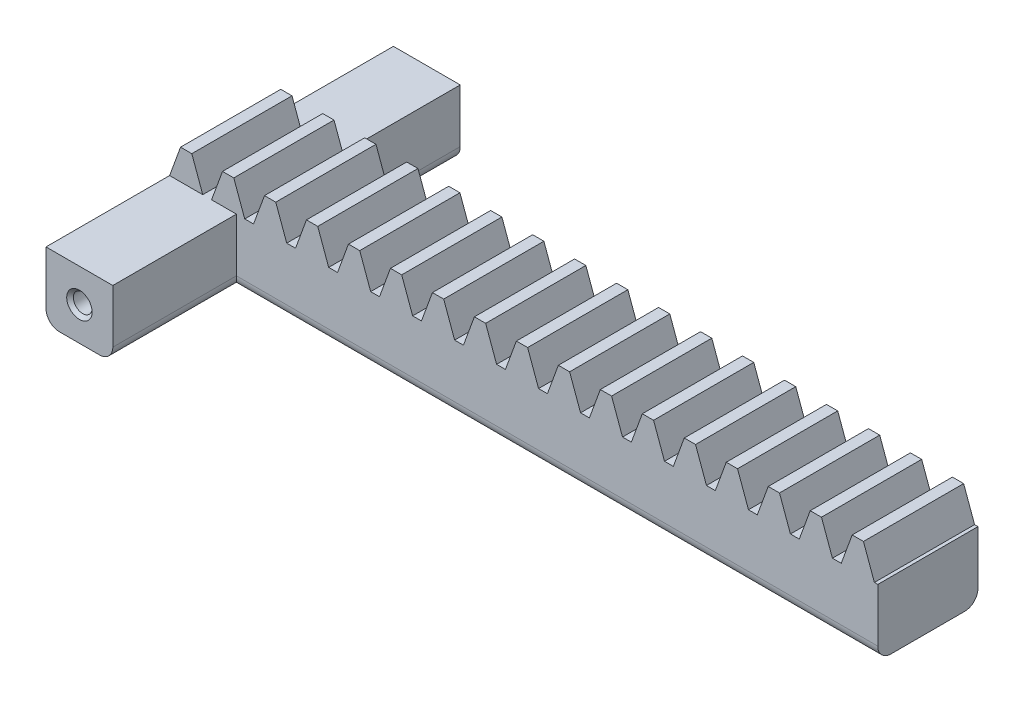
SolidWorks part; units mm, degrees
ref_plane "前视基准面" through (0, 0, 0) normal (0, 0, 1) x (1, 0, 0)
ref_plane "上视基准面" through (0, 0, 0) normal (0, 1, 0) x (1, 0, 0)
ref_plane "右视基准面" through (0, 0, 0) normal (1, 0, 0) x (0, 0, -1)
sketch "草图1" plane through (0, 0, 0) normal (0, 0, 1) x (1, 0, 0)
  line L1 (0, 0) -> (106, 0)
  line L2 (0, 0) -> (0, -10)
  line L3 (0, -10) -> (106, -10)
  line L4 (106, 0) -> (106, -10)
  dimension "D1" = 10
  dimension "L" = 106
extrude "拉伸1" add sketch "草图1" along normal mid plane 15
sketch "草图2" plane through (0, 0, 7.5) normal (0, 0, 1) x (1, 0, 0)
  line L0 (0, 0) -> (1.6379, 4.5)
  line L1 (1.6379, 4.5) -> (3.3236, 4.5)
  line L2 (3.3236, 4.5) -> (4.9614, 0)
  line L3 (106, 0) -> (0, 0) construction
  line L4 (0, 0) -> (4.9614, 0)
  line L5 (0.9099, 2.5) -> (4.0515, 2.5) construction
  dimension "D2" = 70
  dimension "alpha" = 110
  dimension "ha" = 2
  dimension "hf" = 2.5
  dimension "S" = 3.1416
extrude "拉伸2" add sketch "草图2" against normal up to surface (15 mm away) up to face at (53, -5, -7.5)
pattern_linear "阵列(线性)1" count 17 spacing 6.2832 along (1, 0, 0) of "拉伸2"
sketch "草图3" plane through (0, 0, 7.5) normal (0, 0, 1) x (1, 0, 0)
  line L0 (0, 0) -> (0, -10)
  line L1 (0, -10) -> (10, -10)
  line L2 (0, -10) -> (106, -10) construction
  line L3 (10, -10) -> (10, 0)
  line L4 (12.5664, 0) -> (11.2446, 0) construction
  line L5 (10, 0) -> (0, 0)
  dimension "D1" = 10
extrude "凸台-拉伸1" add sketch "草图3" along normal blind 18.5
mirror "镜向1" about plane through (0, 0, 0) normal (0, 0, 1) of "凸台-拉伸1"
sketch "草图4" plane through (0, 0, 26) normal (0, 0, 1) x (1, 0, 0)
  line L0 (0, 0) -> (10, -10) construction
  line L1 (10, 0) -> (0, -10) construction
  line L2 (0, -10) -> (10, -10) construction
  circle A0 centre (5, -5) radius 1.4
  dimension "D1" = 2.8
extrude "切除-拉伸1" cut sketch "草图4" against normal through all
fillet "圆角2" radius 2 2 edges at (58, -10, 7.5) (58, -10, -7.5)
fillet "圆角3" radius 2 3 edges at (10, -10, 15.75) (10, -10, -15.75) (0, -10, 0)
chamfer "倒角1" distance 0.5 angle 45 2 edges at (6.4, -5, 26) (6.4, -5, -26)
sketch "草图5" plane through (0, 0, -7.5) normal (0, 0, -1) x (-1, 0, 0)
  line L0 (-0.9099, 2.5) -> (-104.6735, 2.25) construction
  line L1 (-103.8545, 4.5) -> (-105.4924, 0) construction
equation "\"d\"=\"S@草图2\" * 2"
equation "\"z\"= int(  \"L@草图1\" / (  \"S@草图2\" * 2 ) + 0.5 )"
